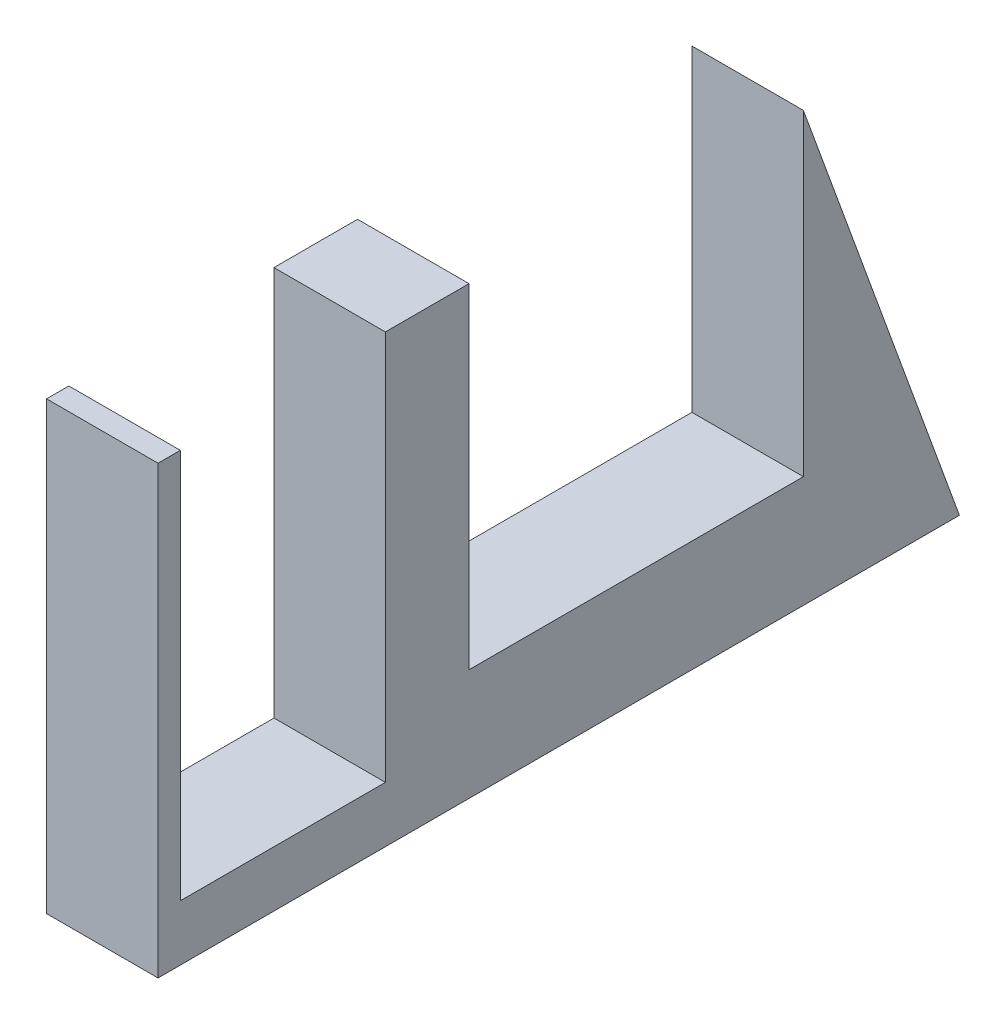
SolidWorks part; units mm, degrees
material "PE High Density"
ref_plane "Front Plane" through (0, 0, 0) normal (0, 0, 1) x (1, 0, 0)
ref_plane "Top Plane" through (0, 0, 0) normal (0, 1, 0) x (1, 0, 0)
ref_plane "Right Plane" through (0, 0, 0) normal (1, 0, 0) x (0, 0, -1)
sketch "Sketch1" plane through (0, 0, 0) normal (1, 0, 0) x (0, 0, -1)
  line L0 (-45.6565, 0) -> (45.6565, 0)
  line L1 (45.6565, 0) -> (27.8765, 48.8501)
  line L2 (27.8765, 48.8501) -> (27.8765, 12.7)
  line L3 (27.8765, 12.7) -> (-10.2235, 12.7)
  line L4 (-10.2235, 12.7) -> (-10.2235, 50.8)
  line L6 (-45.6565, 50.8) -> (-45.6565, 0)
  line L7 (-43.1165, 50.8) -> (-45.6565, 50.8)
  line L9 (-43.1165, 50.8) -> (-43.1165, 6.35)
  line L10 (-43.1165, 6.35) -> (-19.7485, 6.35)
  line L11 (-19.7485, 50.8) -> (-19.7485, 6.35)
  line L12 (-19.7485, 50.8) -> (-10.2235, 50.8)
  dimension "D1" = 70
  dimension "D2" = 38.1
  dimension "D3" = 38.1
  dimension "D4" = 12.7
  dimension "D5" = 17.78
  dimension "D6" = 6.35
  dimension "D7" = 23.368
  dimension "D8" = 9.525
  dimension "D9" = 2.54
extrude "Boss-Extrude1" add sketch "Sketch1" along normal blind 12.7
